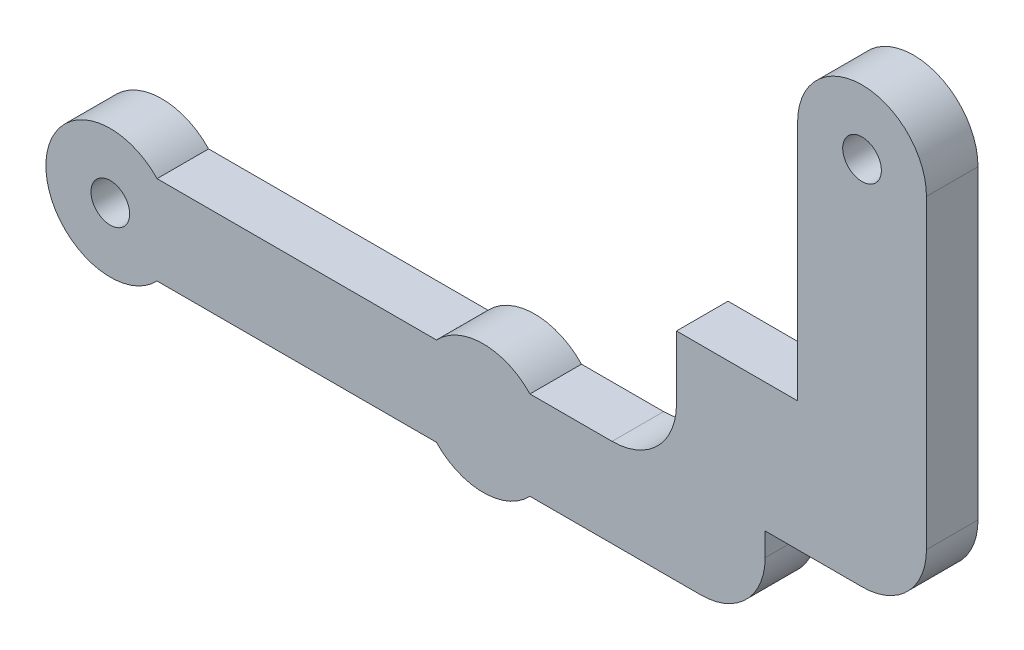
SolidWorks part; units mm, degrees
ref_plane "Alzado" through (0, 0, 0) normal (0, 0, 1) x (1, 0, 0)
ref_plane "Planta" through (0, 0, 0) normal (0, 1, 0) x (1, 0, 0)
ref_plane "Vista lateral" through (0, 0, 0) normal (1, 0, 0) x (0, 0, -1)
sketch "Croquis1" plane through (0, 0, 0) normal (0, 0, 1) x (1, 0, 0)
  line L0 (51.8759, -14.0401) -> (59.3959, -14.0401)
  line L1 (64.3959, -9.0401) -> (64.3959, 14.6999)
  line L4 (54.3959, 14.6999) -> (54.3959, -4.0401)
  line L5 (54.3959, -4.0401) -> (44.9959, -4.0401)
  line L6 (44.9959, 19.6999) -> (44.9959, -8.9601) construction
  line L7 (44.9959, -4.0401) -> (44.9959, -8.9601)
  line L8 (39.9959, -13.9601) -> (33.6245, -13.9601)
  line L10 (4.6845, -20.8401) -> (26.3674, -20.8401)
  line L11 (51.8759, -15.8401) -> (51.8759, -14.0401)
  line L12 (4.6845, -20.8401) -> (26.3674, -20.8401) construction
  line L13 (26.3674, -13.9601) -> (4.6845, -13.9601) construction
  line L14 (64.3959, -9.0401) -> (64.3959, 14.6999) construction
  line L15 (33.6245, -20.8401) -> (46.8759, -20.8401)
  line L16 (26.3674, -13.9601) -> (4.6845, -13.9601)
  arc A0 (33.6245, -13.9601) -> (26.3674, -13.9601) centre (29.9959, -17.4001) ccw
  arc A1 (4.6845, -13.9601) -> (4.6845, -20.8401) centre (1.0559, -17.4001) ccw
  circle A2 centre (59.3959, -9.0401) radius 1.5
  circle A3 centre (59.3959, 1.2399) radius 1.5
  circle A4 centre (59.3959, 14.6999) radius 1.5
  circle A5 centre (29.9959, -17.4001) radius 1.5
  circle A6 centre (1.0559, -17.4001) radius 1.5
  arc A7 (26.3674, -20.8401) -> (33.6245, -20.8401) centre (29.9959, -17.4001) ccw
  arc A8 (64.3959, 14.6999) -> (54.3959, 14.6999) centre (59.3959, 14.6999) ccw
  arc A9 (44.9959, -8.9601) -> (39.9959, -13.9601) centre (39.9959, -8.9601) cw
  arc A10 (64.3959, -9.0401) -> (59.3959, -14.0401) centre (59.3959, -9.0401) cw
  arc A11 (51.8759, -15.8401) -> (46.8759, -20.8401) centre (46.8759, -15.8401) cw
  point P5 (0, 0)
  point P6 (0, 0)
  dimension "D1" = 3
  dimension "D2" = 5
  dimension "D3" = 5
extrude "Saliente-Extruir1" add sketch "Croquis1" along normal blind 4
sketch "Croquis2" plane through (0, 0, 4) normal (0, 0, 1) x (1, 0, 0)
  circle A0 centre (59.3959, 1.2399) radius 1.5
  circle A1 centre (59.3959, -9.0401) radius 1.5
  circle A2 centre (29.9959, -17.4001) radius 1.5
  dimension "D1" = 3
extrude "Saliente-Extruir2" add sketch "Croquis2" against normal blind 1
